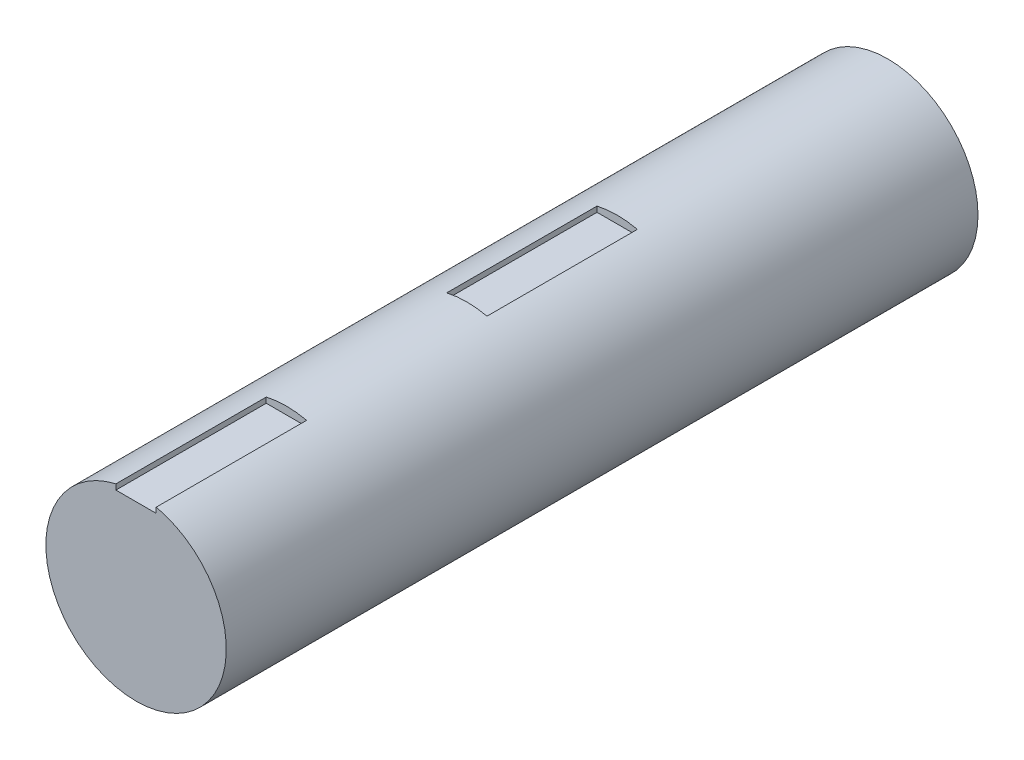
SolidWorks part; units mm, degrees
ref_plane "Front Plane" through (0, 0, 0) normal (0, 0, 1) x (1, 0, 0)
ref_plane "Top Plane" through (0, 0, 0) normal (0, 1, 0) x (1, 0, 0)
ref_plane "Right Plane" through (0, 0, 0) normal (1, 0, 0) x (0, 0, -1)
sketch "Sketch1" plane through (0, 0, 0) normal (0, 0, 1) x (1, 0, 0)
  circle A0 centre (0, 0) radius 30
  dimension "D1" = 60
extrude "Boss-Extrude1" add sketch "Sketch1" along normal mid plane 250
sketch "Sketch2" plane through (0, 0, 125) normal (0, 0, 1) x (1, 0, 0)
  line L0 (0, 0) -> (0, -50000) construction
  line L2 (-6.7098, 34.44) -> (6.7098, 34.44)
  line L3 (-6.7098, 34.44) -> (-6.7098, 27.44)
  line L4 (-6.7098, 27.44) -> (6.7098, 27.44)
  line L5 (6.7098, 34.44) -> (6.7098, 27.44)
  line L6 (-6.7098, 34.44) -> (6.7098, 27.44) construction
  line L7 (-6.7098, 27.44) -> (6.7098, 34.44) construction
  point P3 (0, 30.94)
  dimension "D1" = 7
  dimension "D2" = 30.94
extrude "Cut-Extrude1" cut sketch "Sketch2" against normal blind 50
ref_plane "Plane1" through (0, 0, 15) normal (0, 0, 1) x (1, 0, 0)
sketch "Sketch3" plane through (0, 0, 15) normal (0, 0, 1) x (1, 0, 0)
  line L4 (6.7098, 34.44) -> (-6.7098, 34.44)
  line L5 (6.7098, 27.44) -> (6.7098, 34.44)
  line L6 (-6.7098, 27.44) -> (6.7098, 27.44)
  line L7 (-6.7098, 34.44) -> (-6.7098, 27.44)
  line L8 (6.7098, 34.44) -> (-6.7098, 34.44)
  line L9 (6.7098, 27.44) -> (6.7098, 34.44)
  line L10 (-6.7098, 27.44) -> (6.7098, 27.44)
  line L11 (-6.7098, 34.44) -> (-6.7098, 27.44)
  dimension "D1" = 0
extrude "Cut-Extrude2" cut sketch "Sketch3" against normal blind 50
